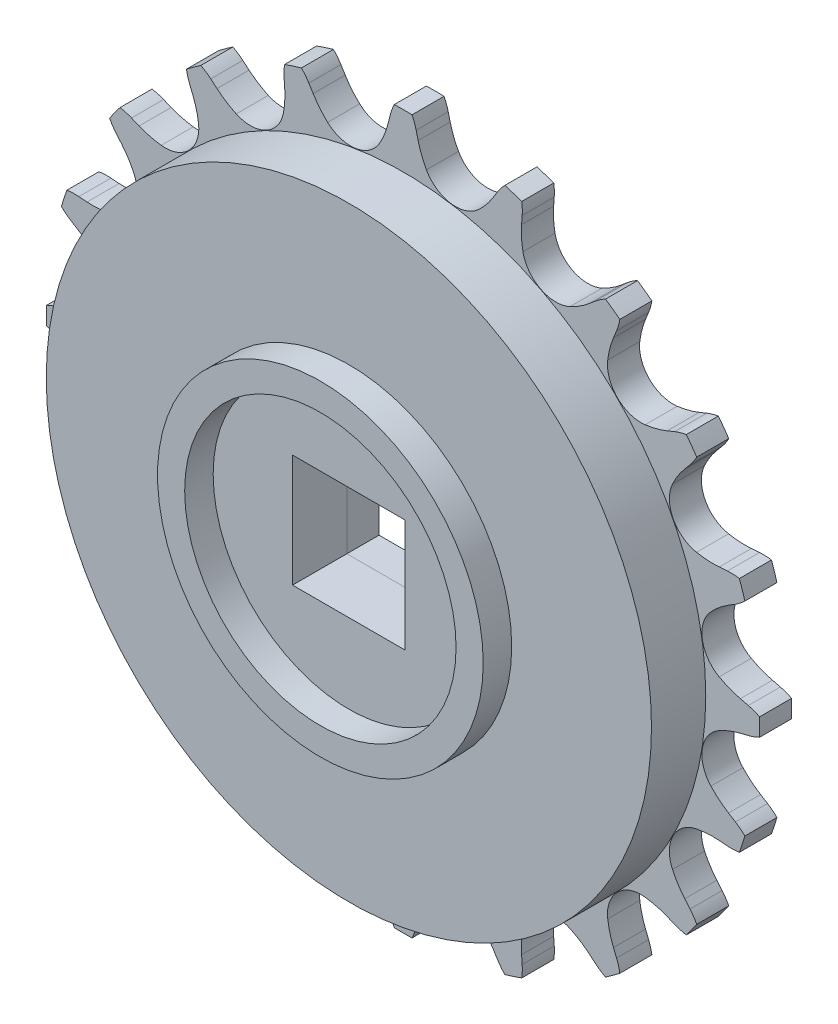
SolidWorks part; units mm, degrees
ref_plane "Front" through (0, 0, 0) normal (0, 0, 1) x (1, 0, 0)
ref_plane "Top" through (0, 0, 0) normal (0, 1, 0) x (1, 0, 0)
ref_plane "Right" through (0, 0, 0) normal (1, 0, 0) x (0, 0, -1)
sketch "Sketch1" plane through (0, 0, 0.25) normal (0, 0, 1) x (1, 0, 0)
  line L0 (-24.4882, 6.9486) -> (-23.9765, 6.6313)
  line L1 (-24.8522, 1.1024) -> (-25.4369, 0.9588)
  line L2 (-25.4369, -0.9588) -> (-24.8522, -1.1024)
  line L3 (-23.9765, -6.6313) -> (-24.4882, -6.9486)
  line L4 (-23.8957, -8.7723) -> (-23.2952, -8.7282)
  line L5 (-20.7538, -13.7159) -> (-21.1425, -14.1758)
  line L6 (-20.0154, -15.7271) -> (-19.4579, -15.4996)
  line L7 (-15.4996, -19.4579) -> (-15.7271, -20.0154)
  line L8 (-14.1758, -21.1425) -> (-13.7159, -20.7538)
  line L9 (-8.7282, -23.2952) -> (-8.7723, -23.8957)
  line L10 (-6.9486, -24.4882) -> (-6.6313, -23.9765)
  line L11 (-1.1024, -24.8522) -> (-0.9588, -25.4369)
  line L12 (0.9588, -25.4369) -> (1.1024, -24.8522)
  line L13 (6.6313, -23.9765) -> (6.9486, -24.4882)
  line L14 (8.7723, -23.8957) -> (8.7282, -23.2952)
  line L15 (13.7159, -20.7538) -> (14.1758, -21.1425)
  line L16 (15.7271, -20.0154) -> (15.4996, -19.4579)
  line L17 (19.4579, -15.4996) -> (20.0154, -15.7271)
  line L18 (21.1425, -14.1758) -> (20.7538, -13.7159)
  line L19 (23.2952, -8.7282) -> (23.8957, -8.7723)
  line L20 (24.4882, -6.9486) -> (23.9765, -6.6313)
  line L21 (24.8522, -1.1024) -> (25.4369, -0.9588)
  line L22 (25.4369, 0.9588) -> (24.8522, 1.1024)
  line L23 (23.9765, 6.6313) -> (24.4882, 6.9486)
  line L24 (23.8957, 8.7723) -> (23.2952, 8.7282)
  line L25 (20.7538, 13.7159) -> (21.1425, 14.1758)
  line L26 (20.0154, 15.7271) -> (19.4579, 15.4996)
  line L27 (15.4996, 19.4579) -> (15.7271, 20.0154)
  line L28 (14.1758, 21.1425) -> (13.7159, 20.7538)
  line L29 (8.7282, 23.2952) -> (8.7723, 23.8957)
  line L30 (6.9486, 24.4882) -> (6.6313, 23.9765)
  line L31 (1.1024, 24.8522) -> (0.9588, 25.4369)
  line L32 (-0.9588, 25.4369) -> (-1.1024, 24.8522)
  line L33 (-6.6313, 23.9765) -> (-6.9486, 24.4882)
  line L34 (-8.7723, 23.8957) -> (-8.7282, 23.2952)
  line L35 (-13.7159, 20.7538) -> (-14.1758, 21.1425)
  line L36 (-15.7271, 20.0154) -> (-15.4996, 19.4579)
  line L37 (-19.4579, 15.4996) -> (-20.0154, 15.7271)
  line L38 (-21.1425, 14.1758) -> (-20.7538, 13.7159)
  line L39 (-23.2952, 8.7282) -> (-23.8957, 8.7723)
  line L40 (6.3855, 9.1279) -> (6.856, 9.5984)
  line L41 (9.5984, 6.856) -> (9.1279, 6.3855)
  line L42 (9.1279, -6.3855) -> (9.5984, -6.856)
  line L43 (6.856, -9.5984) -> (6.3855, -9.1279)
  line L44 (-6.3855, -9.1279) -> (-6.856, -9.5984)
  line L45 (-9.5984, -6.856) -> (-9.1279, -6.3855)
  line L46 (1.9392, 15.5134) -> (1.9392, 10.9696)
  line L47 (-1.9392, 10.9696) -> (-1.9392, 15.5134)
  line L48 (-1.9392, -15.5134) -> (-1.9392, -10.9696)
  line L49 (1.9392, -10.9696) -> (1.9392, -15.5134)
  line L50 (15.5134, -1.9392) -> (10.9696, -1.9392)
  line L51 (10.9696, 1.9392) -> (15.5134, 1.9392)
  line L52 (-15.5134, 1.9392) -> (-10.9696, 1.9392)
  line L53 (-10.9696, -1.9392) -> (-15.5134, -1.9392)
  line L54 (-6.856, 9.5984) -> (-6.3855, 9.1279)
  line L55 (-9.1279, 6.3855) -> (-9.5984, 6.856)
  arc A0 (-25.184, 7.4957) -> (-24.4882, 6.9486) centre (-22.3896, 10.3333) ccw
  arc A1 (-23.9765, 6.6313) -> (-22.6783, 5.565) centre (-27.3234, 1.2333) cw
  arc A2 (-22.6783, 5.565) -> (-23.288, 1.7154) centre (-24.487, 3.8784) cw
  arc A3 (-23.288, 1.7154) -> (-24.8522, 1.1024) centre (-26.3672, 7.2704) cw
  arc A4 (-25.4369, 0.9588) -> (-26.2677, 0.6534) centre (-24.487, -2.9088) ccw
  arc A5 (-26.2677, 0.6534) -> (-26.2677, -0.6534) centre (0, 0) ccw
  arc A6 (-26.2677, -0.6534) -> (-25.4369, -0.9588) centre (-24.487, 2.9088) ccw
  arc A7 (-24.8522, -1.1024) -> (-23.288, -1.7154) centre (-26.3672, -7.2704) cw
  arc A8 (-23.288, -1.7154) -> (-22.6783, -5.565) centre (-24.487, -3.8784) cw
  arc A9 (-22.6783, -5.565) -> (-23.9765, -6.6313) centre (-27.3234, -1.2333) cw
  arc A10 (-24.4882, -6.9486) -> (-25.184, -7.4957) centre (-22.3896, -10.3333) ccw
  arc A11 (-25.184, -7.4957) -> (-24.7802, -8.7386) centre (0, 0) ccw
  arc A12 (-24.7802, -8.7386) -> (-23.8957, -8.7723) centre (-24.1873, -4.8005) ccw
  arc A13 (-23.2952, -8.7282) -> (-21.6181, -8.8278) centre (-22.83, -15.0625) cw
  arc A14 (-21.6181, -8.8278) -> (-19.8487, -12.3006) centre (-22.09, -11.2554) cw
  arc A15 (-19.8487, -12.3006) -> (-20.7538, -13.7159) centre (-25.605, -9.6164) cw
  arc A16 (-21.1425, -14.1758) -> (-21.6351, -14.9112) centre (-18.1006, -16.7463) ccw
  arc A17 (-21.6351, -14.9112) -> (-20.867, -15.9684) centre (0, 0) ccw
  arc A18 (-20.867, -15.9684) -> (-20.0154, -15.7271) centre (-21.5201, -12.0398) ccw
  arc A19 (-19.4579, -15.4996) -> (-17.8321, -15.0761) centre (-17.0581, -21.3802) cw
  arc A20 (-17.8321, -15.0761) -> (-15.0761, -17.8321) centre (-17.5307, -17.5307) cw
  arc A21 (-15.0761, -17.8321) -> (-15.4996, -19.4579) centre (-21.3802, -17.0581) cw
  arc A22 (-15.7271, -20.0154) -> (-15.9684, -20.867) centre (-12.0398, -21.5201) ccw
  arc A23 (-15.9684, -20.867) -> (-14.9112, -21.6351) centre (0, 0) ccw
  arc A24 (-14.9112, -21.6351) -> (-14.1758, -21.1425) centre (-16.7463, -18.1006) ccw
  arc A25 (-13.7159, -20.7538) -> (-12.3006, -19.8487) centre (-9.6164, -25.605) cw
  arc A26 (-12.3006, -19.8487) -> (-8.8278, -21.6181) centre (-11.2554, -22.09) cw
  arc A27 (-8.8278, -21.6181) -> (-8.7282, -23.2952) centre (-15.0625, -22.83) cw
  arc A28 (-8.7723, -23.8957) -> (-8.7386, -24.7802) centre (-4.8005, -24.1873) ccw
  arc A29 (-8.7386, -24.7802) -> (-7.4957, -25.184) centre (0, 0) ccw
  arc A30 (-7.4957, -25.184) -> (-6.9486, -24.4882) centre (-10.3333, -22.3896) ccw
  arc A31 (-6.6313, -23.9765) -> (-5.565, -22.6783) centre (-1.2333, -27.3234) cw
  arc A32 (-5.565, -22.6783) -> (-1.7154, -23.288) centre (-3.8784, -24.487) cw
  arc A33 (-1.7154, -23.288) -> (-1.1024, -24.8522) centre (-7.2704, -26.3672) cw
  arc A34 (-0.9588, -25.4369) -> (-0.6534, -26.2677) centre (2.9088, -24.487) ccw
  arc A35 (-0.6534, -26.2677) -> (0.6534, -26.2677) centre (0, 0) ccw
  arc A36 (0.6534, -26.2677) -> (0.9588, -25.4369) centre (-2.9088, -24.487) ccw
  arc A37 (1.1024, -24.8522) -> (1.7154, -23.288) centre (7.2704, -26.3672) cw
  arc A38 (1.7154, -23.288) -> (5.565, -22.6783) centre (3.8784, -24.487) cw
  arc A39 (5.565, -22.6783) -> (6.6313, -23.9765) centre (1.2333, -27.3234) cw
  arc A40 (6.9486, -24.4882) -> (7.4957, -25.184) centre (10.3333, -22.3896) ccw
  arc A41 (7.4957, -25.184) -> (8.7386, -24.7802) centre (0, 0) ccw
  arc A42 (8.7386, -24.7802) -> (8.7723, -23.8957) centre (4.8005, -24.1873) ccw
  arc A43 (8.7282, -23.2952) -> (8.8278, -21.6181) centre (15.0625, -22.83) cw
  arc A44 (8.8278, -21.6181) -> (12.3006, -19.8487) centre (11.2554, -22.09) cw
  arc A45 (12.3006, -19.8487) -> (13.7159, -20.7538) centre (9.6164, -25.605) cw
  arc A46 (14.1758, -21.1425) -> (14.9112, -21.6351) centre (16.7463, -18.1006) ccw
  arc A47 (14.9112, -21.6351) -> (15.9684, -20.867) centre (0, 0) ccw
  arc A48 (15.9684, -20.867) -> (15.7271, -20.0154) centre (12.0398, -21.5201) ccw
  arc A49 (15.4996, -19.4579) -> (15.0761, -17.8321) centre (21.3802, -17.0581) cw
  arc A50 (15.0761, -17.8321) -> (17.8321, -15.0761) centre (17.5307, -17.5307) cw
  arc A51 (17.8321, -15.0761) -> (19.4579, -15.4996) centre (17.0581, -21.3802) cw
  arc A52 (20.0154, -15.7271) -> (20.867, -15.9684) centre (21.5201, -12.0398) ccw
  arc A53 (20.867, -15.9684) -> (21.6351, -14.9112) centre (0, 0) ccw
  arc A54 (21.6351, -14.9112) -> (21.1425, -14.1758) centre (18.1006, -16.7463) ccw
  arc A55 (20.7538, -13.7159) -> (19.8487, -12.3006) centre (25.605, -9.6164) cw
  arc A56 (19.8487, -12.3006) -> (21.6181, -8.8278) centre (22.09, -11.2554) cw
  arc A57 (21.6181, -8.8278) -> (23.2952, -8.7282) centre (22.83, -15.0625) cw
  arc A58 (23.8957, -8.7723) -> (24.7802, -8.7386) centre (24.1873, -4.8005) ccw
  arc A59 (24.7802, -8.7386) -> (25.184, -7.4957) centre (0, 0) ccw
  arc A60 (25.184, -7.4957) -> (24.4882, -6.9486) centre (22.3896, -10.3333) ccw
  arc A61 (23.9765, -6.6313) -> (22.6783, -5.565) centre (27.3234, -1.2333) cw
  arc A62 (22.6783, -5.565) -> (23.288, -1.7154) centre (24.487, -3.8784) cw
  arc A63 (23.288, -1.7154) -> (24.8522, -1.1024) centre (26.3672, -7.2704) cw
  arc A64 (25.4369, -0.9588) -> (26.2677, -0.6534) centre (24.487, 2.9088) ccw
  arc A65 (26.2677, -0.6534) -> (26.2677, 0.6534) centre (0, 0) ccw
  arc A66 (26.2677, 0.6534) -> (25.4369, 0.9588) centre (24.487, -2.9088) ccw
  arc A67 (24.8522, 1.1024) -> (23.288, 1.7154) centre (26.3672, 7.2704) cw
  arc A68 (23.288, 1.7154) -> (22.6783, 5.565) centre (24.487, 3.8784) cw
  arc A69 (22.6783, 5.565) -> (23.9765, 6.6313) centre (27.3234, 1.2333) cw
  arc A70 (24.4882, 6.9486) -> (25.184, 7.4957) centre (22.3896, 10.3333) ccw
  arc A71 (25.184, 7.4957) -> (24.7802, 8.7386) centre (0, 0) ccw
  arc A72 (24.7802, 8.7386) -> (23.8957, 8.7723) centre (24.1873, 4.8005) ccw
  arc A73 (23.2952, 8.7282) -> (21.6181, 8.8278) centre (22.83, 15.0625) cw
  arc A74 (21.6181, 8.8278) -> (19.8487, 12.3006) centre (22.09, 11.2554) cw
  arc A75 (19.8487, 12.3006) -> (20.7538, 13.7159) centre (25.605, 9.6164) cw
  arc A76 (21.1425, 14.1758) -> (21.6351, 14.9112) centre (18.1006, 16.7463) ccw
  arc A77 (21.6351, 14.9112) -> (20.867, 15.9684) centre (0, 0) ccw
  arc A78 (20.867, 15.9684) -> (20.0154, 15.7271) centre (21.5201, 12.0398) ccw
  arc A79 (19.4579, 15.4996) -> (17.8321, 15.0761) centre (17.0581, 21.3802) cw
  arc A80 (17.8321, 15.0761) -> (15.0761, 17.8321) centre (17.5307, 17.5307) cw
  arc A81 (15.0761, 17.8321) -> (15.4996, 19.4579) centre (21.3802, 17.0581) cw
  arc A82 (15.7271, 20.0154) -> (15.9684, 20.867) centre (12.0398, 21.5201) ccw
  arc A83 (15.9684, 20.867) -> (14.9112, 21.6351) centre (0, 0) ccw
  arc A84 (14.9112, 21.6351) -> (14.1758, 21.1425) centre (16.7463, 18.1006) ccw
  arc A85 (13.7159, 20.7538) -> (12.3006, 19.8487) centre (9.6164, 25.605) cw
  arc A86 (12.3006, 19.8487) -> (8.8278, 21.6181) centre (11.2554, 22.09) cw
  arc A87 (8.8278, 21.6181) -> (8.7282, 23.2952) centre (15.0625, 22.83) cw
  arc A88 (8.7723, 23.8957) -> (8.7386, 24.7802) centre (4.8005, 24.1873) ccw
  arc A89 (8.7386, 24.7802) -> (7.4957, 25.184) centre (0, 0) ccw
  arc A90 (7.4957, 25.184) -> (6.9486, 24.4882) centre (10.3333, 22.3896) ccw
  arc A91 (6.6313, 23.9765) -> (5.565, 22.6783) centre (1.2333, 27.3234) cw
  arc A92 (5.565, 22.6783) -> (1.7154, 23.288) centre (3.8784, 24.487) cw
  arc A93 (1.7154, 23.288) -> (1.1024, 24.8522) centre (7.2704, 26.3672) cw
  arc A94 (0.9588, 25.4369) -> (0.6534, 26.2677) centre (-2.9088, 24.487) ccw
  arc A95 (0.6534, 26.2677) -> (-0.6534, 26.2677) centre (0, 0) ccw
  arc A96 (-0.6534, 26.2677) -> (-0.9588, 25.4369) centre (2.9088, 24.487) ccw
  arc A97 (-1.1024, 24.8522) -> (-1.7154, 23.288) centre (-7.2704, 26.3672) cw
  arc A98 (-1.7154, 23.288) -> (-5.565, 22.6783) centre (-3.8784, 24.487) cw
  arc A99 (-5.565, 22.6783) -> (-6.6313, 23.9765) centre (-1.2333, 27.3234) cw
  arc A100 (-6.9486, 24.4882) -> (-7.4957, 25.184) centre (-10.3333, 22.3896) ccw
  arc A101 (-7.4957, 25.184) -> (-8.7386, 24.7802) centre (0, 0) ccw
  arc A102 (-8.7386, 24.7802) -> (-8.7723, 23.8957) centre (-4.8005, 24.1873) ccw
  arc A103 (-8.7282, 23.2952) -> (-8.8278, 21.6181) centre (-15.0625, 22.83) cw
  arc A104 (-8.8278, 21.6181) -> (-12.3006, 19.8487) centre (-11.2554, 22.09) cw
  arc A105 (-12.3006, 19.8487) -> (-13.7159, 20.7538) centre (-9.6164, 25.605) cw
  arc A106 (-14.1758, 21.1425) -> (-14.9112, 21.6351) centre (-16.7463, 18.1006) ccw
  arc A107 (-14.9112, 21.6351) -> (-15.9684, 20.867) centre (0, 0) ccw
  arc A108 (-15.9684, 20.867) -> (-15.7271, 20.0154) centre (-12.0398, 21.5201) ccw
  arc A109 (-15.4996, 19.4579) -> (-15.0761, 17.8321) centre (-21.3802, 17.0581) cw
  arc A110 (-15.0761, 17.8321) -> (-17.8321, 15.0761) centre (-17.5307, 17.5307) cw
  arc A111 (-17.8321, 15.0761) -> (-19.4579, 15.4996) centre (-17.0581, 21.3802) cw
  arc A112 (-20.0154, 15.7271) -> (-20.867, 15.9684) centre (-21.5201, 12.0398) ccw
  arc A113 (-20.867, 15.9684) -> (-21.6351, 14.9112) centre (0, 0) ccw
  arc A114 (-21.6351, 14.9112) -> (-21.1425, 14.1758) centre (-18.1006, 16.7463) ccw
  arc A115 (-20.7538, 13.7159) -> (-19.8487, 12.3006) centre (-25.605, 9.6164) cw
  arc A116 (-19.8487, 12.3006) -> (-21.6181, 8.8278) centre (-22.09, 11.2554) cw
  arc A117 (-21.6181, 8.8278) -> (-23.2952, 8.7282) centre (-22.83, 15.0625) cw
  arc A118 (-23.8957, 8.7723) -> (-24.7802, 8.7386) centre (-24.1873, 4.8005) ccw
  arc A119 (-24.7802, 8.7386) -> (-25.184, 7.4957) centre (0, 0) ccw
  circle A120 centre (0, 0) radius 6.7871
  arc A121 (9.1279, 6.3855) -> (6.3855, 9.1279) centre (7.7567, 7.7567) cw
  arc A122 (6.856, 9.5984) -> (9.5984, 6.856) centre (8.2272, 8.2272) cw
  arc A123 (6.3855, -9.1279) -> (9.1279, -6.3855) centre (7.7567, -7.7567) cw
  arc A124 (9.5984, -6.856) -> (6.856, -9.5984) centre (8.2272, -8.2272) cw
  arc A125 (-9.1279, -6.3855) -> (-6.3855, -9.1279) centre (-7.7567, -7.7567) cw
  arc A126 (-6.856, -9.5984) -> (-9.5984, -6.856) centre (-8.2272, -8.2272) cw
  arc A127 (1.9392, 10.9696) -> (-1.9392, 10.9696) centre (0, 10.9696) cw
  arc A128 (-1.9392, 15.5134) -> (1.9392, 15.5134) centre (0, 15.5134) cw
  arc A129 (-1.9392, -10.9696) -> (1.9392, -10.9696) centre (0, -10.9696) cw
  arc A130 (1.9392, -15.5134) -> (-1.9392, -15.5134) centre (0, -15.5134) cw
  arc A131 (10.9696, -1.9392) -> (10.9696, 1.9392) centre (10.9696, 0) cw
  arc A132 (15.5134, 1.9392) -> (15.5134, -1.9392) centre (15.5134, 0) cw
  arc A133 (-10.9696, 1.9392) -> (-10.9696, -1.9392) centre (-10.9696, 0) cw
  arc A134 (-15.5134, -1.9392) -> (-15.5134, 1.9392) centre (-15.5134, 0) cw
  arc A135 (-6.3855, 9.1279) -> (-9.1279, 6.3855) centre (-7.7567, 7.7567) cw
  arc A136 (-9.5984, 6.856) -> (-6.856, 9.5984) centre (-8.2272, 8.2272) cw
extrude "Boss-Extrude1" add sketch "Sketch1" against normal blind 2.3622
sketch "Sketch2" plane through (0, 0, 0.25) normal (0, 0, 1) x (1, 0, 0)
  circle A0 centre (0, 0) radius 18
extrude "Boss-Extrude2" add sketch "Sketch2" against normal blind 2.4 separate body
sketch "Sketch6" plane through (0, 0, 0.25) normal (0, 0, 1) x (1, 0, 0)
  line L3 (-4.365, -4.365) -> (4.2394, -4.365)
  line L4 (4.2394, 4.2394) -> (4.2394, -4.365)
  circle A0 centre (0, 0) radius 17
  circle A1 centre (0, 0) radius 22.3005
extrude "Boss-Extrude3" add sketch "Sketch6" along normal blind 4 separate body
sketch "Sketch12" plane through (0, 0, -2.15) normal (0, 0, -1) x (-1, 0, 0)
  circle A0 centre (0, 0) radius 14
sketch "Sketch8" plane through (0, 0, 4.25) normal (0, 0, 1) x (1, 0, 0)
  line L1 (-4.15, -4.15) -> (4.15, -4.15)
  line L2 (-4.15, -4.15) -> (-4.15, 4.15)
  line L3 (-4.15, 4.15) -> (4.15, 4.15)
  line L4 (4.15, -4.15) -> (4.15, 4.15)
  line L5 (-4.15, -4.15) -> (4.15, 4.15) construction
  line L6 (-4.15, 4.15) -> (4.15, -4.15) construction
  point P0 (0, 0)
  dimension "D1" = 8.3
  dimension "D2" = 8.3
extrude "Cut-Extrude1" cut sketch "Sketch8" against normal through all
ref_plane "Plane1" [suppressed] through (14, 0, 0) normal (1, 0, 0) x (0, 0, -1)
sketch "Sketch16" plane through (-4.15, 0, 0) normal (1, 0, 0) x (0, 0, -1)
  line L0 (2.15, -4.15) -> (-0.25, -4.15) construction
  line L1 (11.1227, 4.1) -> (1.1227, 4.1)
  line L2 (11.1227, 4.1) -> (11.1227, -4.15)
  line L3 (11.1227, -4.15) -> (1.1227, -4.15)
  line L4 (1.1227, 4.1) -> (1.1227, -4.15)
  dimension "D1" = 10
extrude "Boss-Extrude6" add sketch "Sketch16" against normal blind 9.7416
ref_plane "Plane3" through (-0.05, 0, 0) normal (1, 0, 0) x (0, 0, -1)
mirror "Mirror1" about plane through (-0.05, 0, 0) normal (1, 0, 0) of "Boss-Extrude6"
sketch "Sketch13" [suppressed] plane through (14, 0, 0) normal (1, 0, 0) x (0, 0, -1)
  line L1 (11.1227, -4.1) -> (11.1227, 4.1) construction
  circle A0 centre (8.1227, 0) radius 2.1
  dimension "D2" = 4.2
  dimension "D1" = 3
extrude "Cut-Extrude3" [suppressed] cut sketch "Sketch13" against normal through all and the other way through all
sketch "Sketch17" plane through (0, 0, 4.25) normal (0, 0, 1) x (1, 0, 0)
  circle A0 centre (0, 0) radius 10
extrude "Extrude-Thin1" add sketch "Sketch17" along normal blind 2.1 thin
sketch "Sketch18" plane through (0, 0, -11.1227) normal (0, 0, -1) x (-1, 0, 0)
  circle A0 centre (0, 0) radius 53.2213
extrude "Cut-Extrude4" cut sketch "Sketch18" against normal blind 9
